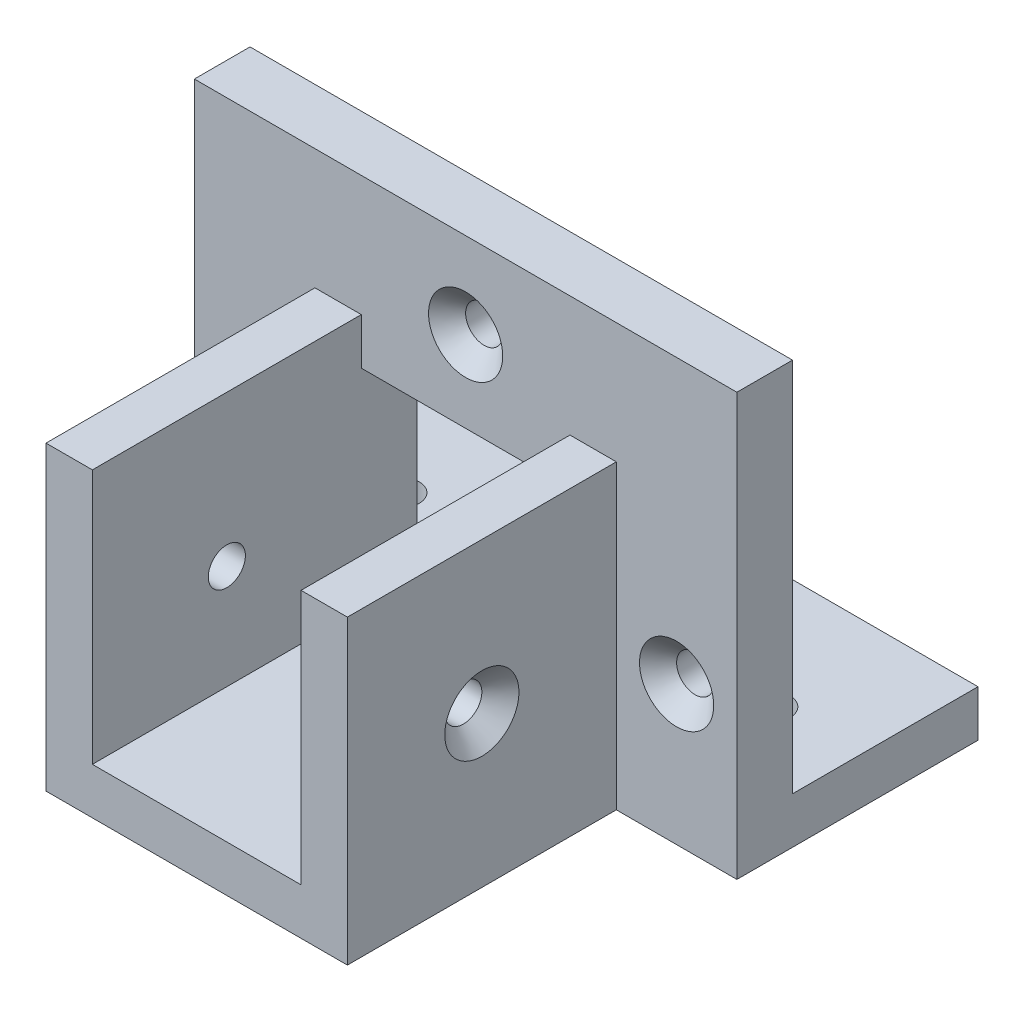
SolidWorks part; units mm, degrees
ref_plane "Top Plane" through (0, 0, 0) normal (0, 0, 1) x (1, 0, 0)
ref_plane "Right Plane" through (0, 0, 0) normal (0, 1, 0) x (1, 0, 0)
ref_plane "Front Plane" through (0, 0, 0) normal (1, 0, 0) x (0, 0, -1)
sketch "Sketch1" plane through (0, 0, 0) normal (0, 0, 1) x (1, 0, 0)
  line L0 (-11.25, -11.25) -> (11.25, 11.25) construction
  line L1 (-11.25, -11.25) -> (11.25, -11.25)
  line L2 (-11.25, -11.25) -> (-11.25, 11.25)
  line L3 (-11.25, 11.25) -> (11.25, 11.25)
  line L4 (11.25, -11.25) -> (11.25, 11.25)
  line L6 (-16.25, -16.25) -> (16.25, -16.25)
  line L7 (-16.25, -16.25) -> (-16.25, 16.25)
  line L8 (-16.25, 16.25) -> (16.25, 16.25)
  line L9 (16.25, -16.25) -> (16.25, 16.25)
  line L10 (-16.25, -16.25) -> (16.25, 16.25) construction
  line L11 (-16.25, 16.25) -> (16.25, -16.25) construction
  point P4 (0, 0)
  dimension "D1" = 22.5
  dimension "D2" = 5
extrude "Boss-Extrude1" add sketch "Sketch1" along normal blind 35
sketch "Sketch2" plane through (0, 0, 0) normal (0, 0, -1) x (-1, 0, 0)
  line L0 (0, 16.25) -> (0, 29.25) construction
  line L1 (-16.25, -16.25) -> (-29.25, -16.25)
  line L2 (-16.25, -16.25) -> (-16.25, 16.25)
  line L4 (-29.25, -16.25) -> (-29.25, 29.25)
  line L5 (-29.25, 29.25) -> (29.25, 29.25)
  line L7 (-16.25, 16.25) -> (16.25, 16.25)
  line L10 (29.25, 29.25) -> (29.25, -16.25)
  line L11 (29.25, -16.25) -> (16.25, -16.25)
  line L12 (16.25, 16.25) -> (16.25, -16.25)
  dimension "D1" = 13
extrude "Boss-Extrude2" add sketch "Sketch2" against normal blind 6
sketch "Sketch3" plane through (0, 0, 6) normal (0, 0, 1) x (1, 0, 0)
  line L0 (-16.25, -1.25) -> (-29.25, -1.25) construction
  line L2 (-29.25, -16.25) -> (-29.25, 29.25) construction
  line L3 (16.25, -1.25) -> (29.25, -1.25) construction
  line L5 (29.25, 29.25) -> (29.25, -16.25) construction
  line L7 (16.25, -16.25) -> (16.25, 16.25) construction
  line L8 (-16.25, 16.25) -> (-16.25, -16.25) construction
  line L9 (-11.25, -11.25) -> (11.25, -11.25) construction
  line L10 (0, 20) -> (0, 16.25) construction
  line L11 (16.25, 16.25) -> (-16.25, 16.25) construction
  circle A0 centre (-22.75, -1.25) radius 2
  circle A1 centre (0, 20) radius 2
  circle A2 centre (22.75, -1.25) radius 2
  dimension "D1" = 4
  dimension "D2" = 20
  dimension "D3" = 10
extrude "Cut-Extrude1" cut sketch "Sketch3" against normal through all
sketch "Sketch4" plane through (0, 0, 35) normal (0, 0, 1) x (1, 0, 0)
  line L0 (16.25, 16.25) -> (-16.25, 16.25) construction
  line L1 (-11.25, 11.25) -> (11.25, 11.25)
  line L2 (-11.25, 11.25) -> (-11.25, 16.25)
  line L3 (-11.25, 16.25) -> (11.25, 16.25)
  line L4 (11.25, 11.25) -> (11.25, 16.25)
  line L5 (11.25, 11.25) -> (-11.25, 11.25) construction
  point P8 (11.1491, 11.5)
extrude "Cut-Extrude2" cut sketch "Sketch4" against normal up to surface (29 mm away) up to face at (-20.75, -1.25, 6)
sketch "Sketch5" plane through (16.25, 0, 0) normal (1, 0, 0) x (0, 0, -1)
  line L0 (-20.5, 16.25) -> (-20.5, -16.25) construction
  line L1 (-35, 16.25) -> (-6, 16.25) construction
  line L2 (-35, -16.25) -> (-6, -16.25) construction
  circle A0 centre (-20.5, 0) radius 2
  dimension "D1" = 4
sketch "Sketch6" plane through (0, 0, 0) normal (0, 0, -1) x (-1, 0, 0)
  line L0 (-29.25, 29.25) -> (-29.25, -16.25) construction
  line L1 (29.25, -16.25) -> (-29.25, -16.25)
  line L2 (29.25, -16.25) -> (29.25, -11.25)
  line L3 (29.25, -11.25) -> (-29.25, -11.25)
  line L4 (-29.25, -16.25) -> (-29.25, -11.25)
extrude "Boss-Extrude3" add sketch "Sketch6" along normal blind 20
extrude "Cut-Extrude3" cut sketch "Sketch5" against normal through all
sketch "Sketch7" plane through (0, -16.25, 0) normal (0, -1, 0) x (1, 0, 0)
  line L0 (-29.25, -7) -> (29.25, -7) construction
  line L1 (-29.25, 6) -> (-29.25, -20) construction
  line L2 (29.25, 6) -> (29.25, -20) construction
  line L3 (-20, -5) -> (20, -5) construction
  line L4 (0, -5) -> (0, 0) construction
  line L5 (0, 0) -> (0, 20.5) construction
  line L8 (-16.25, 35) -> (-16.25, 6) construction
  line L9 (-16.25, 20.5) -> (16.25, 20.5) construction
  line L10 (16.25, 35) -> (16.25, 6) construction
  circle A0 centre (-20, -7) radius 2
  circle A1 centre (20, -7) radius 2
  circle A2 centre (0, 20.5) radius 2
  point P24 (0, 18)
  dimension "D1" = 4
  dimension "D2" = 40
extrude "Cut-Extrude4" cut sketch "Sketch7" against normal through all
chamfer "Chamfer1" distance 2 angle 45 8 edges at (2, 20, 6) (-20.75, -1.25, 6) (24.75, -1.25, 6) (20, -16.25, -9) (0, -16.25, 18.5) (-20, -16.25, -9) (-16.25, 0, 18.5) (16.25, 0, 18.5)
